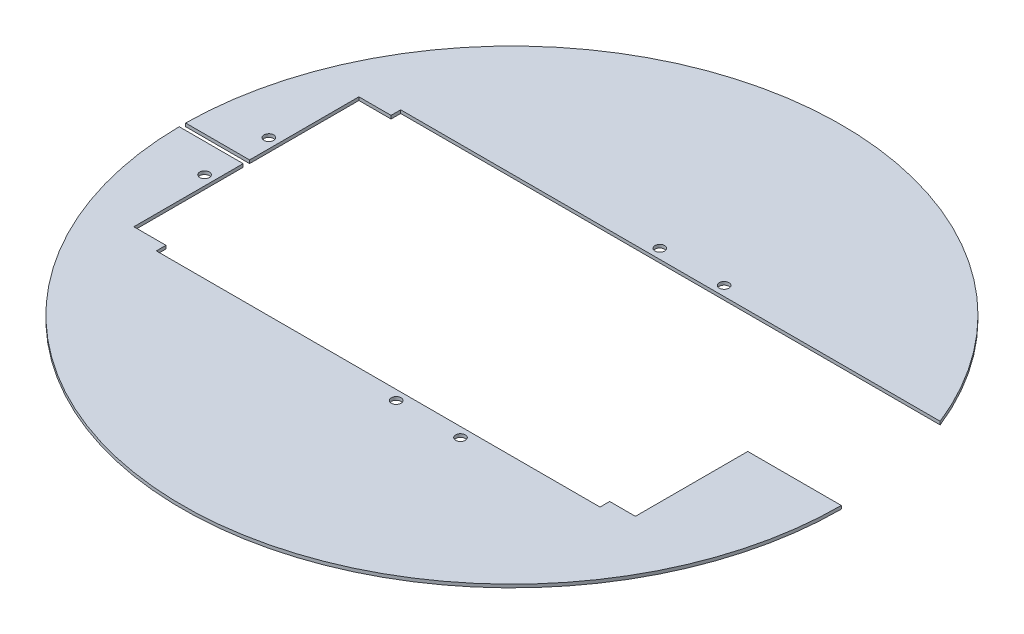
SolidWorks part; units mm, degrees
material "Thornel Mat VMA"
ref_plane "前视基准面" through (0, 0, 0) normal (0, 0, 1) x (1, 0, 0)
ref_plane "上视基准面" through (0, 0, 0) normal (0, 1, 0) x (1, 0, 0)
ref_plane "右视基准面" through (0, 0, 0) normal (1, 0, 0) x (0, 0, -1)
sketch "草图1" plane through (0, 0, 0) normal (0, 1, 0) x (1, 0, 0)
  line L0 (-82.6, 35) -> (-82.6, -35)
  line L1 (-82.6, 0) -> (0, 0) construction
  line L2 (73.4, 35) -> (73.4, -35)
  line L3 (-82.6, 35) -> (73.4, 35) construction
  line L4 (-82.6, -35) -> (73.4, -35) construction
  line L5 (-82.6, 35) -> (-72.6, 35)
  line L6 (73.4, 35) -> (65.4, 35)
  line L7 (-72.6, 35) -> (-72.6, 38)
  line L8 (-72.6, 38) -> (65.4, 38)
  line L9 (65.4, 38) -> (65.4, 35)
  line L10 (73.4, -35) -> (65.4, -35)
  line L11 (65.4, -38) -> (65.4, -35)
  line L12 (-72.6, -35) -> (-72.6, -38)
  line L13 (-72.6, -38) -> (65.4, -38)
  line L14 (-82.6, -35) -> (-72.6, -35)
  line L15 (-47.5, 45) -> (-47.5, -45) construction
  line L16 (-47.5, -45) -> (47.5, -45) construction
  line L17 (47.5, -45) -> (47.5, 45) construction
  line L18 (47.5, 45) -> (-47.5, 45) construction
  circle A0 centre (0, 0) radius 102.5
  point P20 (0, 45)
  point P21 (-47.5, 0)
  dimension "D1" = 205
  dimension "D2" = 82.6
  dimension "D3" = 70
  dimension "D4" = 73.4
  dimension "D5" = 3
  dimension "D6" = 10
  dimension "D7" = 8
  dimension "D8" = 90
  dimension "D9" = 95
extrude "凸台-拉伸1" add sketch "草图1" along normal blind 1
sketch "草图2" plane through (0, 1, 0) normal (0, 1, 0) x (1, 0, 0)
  line L0 (-82.6, 35) -> (-82.6, -35) construction
  line L1 (73.4, 0.05) -> (121.3337, 0.05)
  line L2 (73.4, 0.05) -> (73.4, -0.05)
  line L3 (73.4, -0.05) -> (121.3337, -0.05)
  line L4 (121.3337, 0.05) -> (121.3337, -0.05)
  line L5 (-82.6, 1) -> (-189.3873, 1)
  line L6 (-82.6, 1) -> (-82.6, -1)
  line L7 (-82.6, -1) -> (-189.3873, -1)
  line L8 (-189.3873, 1) -> (-189.3873, -1)
  line L10 (73.4, -35) -> (73.4, 35) construction
  point P16 (-82.6, 0)
  point P18 (73.4, 0)
  dimension "D1" = 2
  dimension "D2" = 0.1
extrude "切除-拉伸1" cut sketch "草图2" against normal through all
sketch "草图5" plane through (0, 1, 0) normal (0, 1, 0) x (1, 0, 0)
  line L1 (102.5, 0.05) -> (65.4, 0.05)
  line L2 (102.5, 0.05) -> (102.5, 38)
  line L3 (102.5, 38) -> (65.4, 38)
  line L4 (65.4, 0.05) -> (65.4, 38)
extrude "切除-拉伸4" cut sketch "草图5" against normal through all
sketch "草图6" plane through (0, 1, 0) normal (0, 1, 0) x (1, 0, 0)
  line L0 (0, -102.5) -> (0, 102.5) construction
  line L1 (0, 0) -> (102.5, 0) construction
  line L3 (95.1959, 38) -> (-72.6, 38) construction
  line L4 (-82.6, 35) -> (-82.6, 1) construction
  arc A1 (-102.4951, -1) -> (102.5, -0.05) centre (0, 0) ccw construction
  circle A2 centre (5, 41) radius 1.5
  circle A3 centre (25, 41) radius 1.5
  circle A4 centre (25, -41) radius 1.5
  circle A5 centre (5, -41) radius 1.5
  circle A6 centre (-85.6, 10) radius 1.5
  circle A7 centre (-85.6, -10) radius 1.5
  arc A9 (95.1959, 38) -> (-102.4951, 1) centre (0, 0) ccw construction
  dimension "D1" = 20
  dimension "D3" = 3
  dimension "D4" = 3
  dimension "D2" = 3
  dimension "D5" = 20
  dimension "D6" = 3
  dimension "D7" = 5
extrude "切除-拉伸5" cut sketch "草图6" against normal through all
